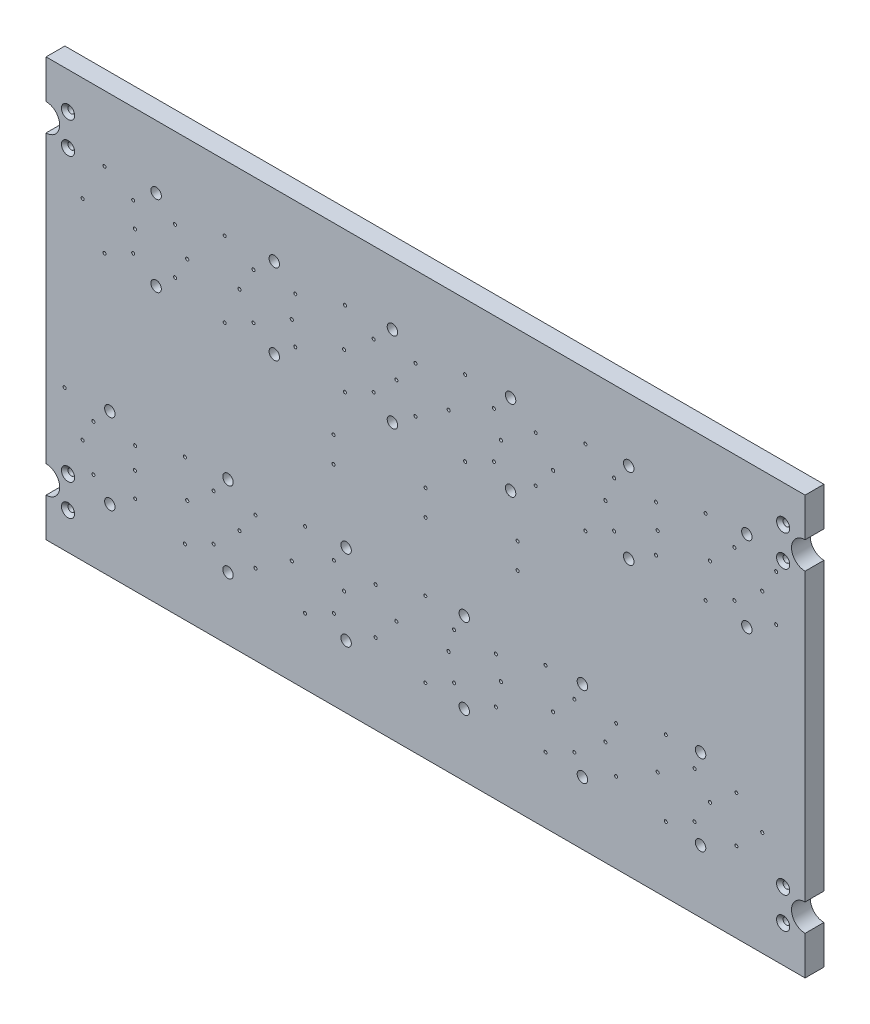
SolidWorks part; units mm, degrees
material "Balsa"
ref_plane "Спереди" through (0, 0, 0) normal (0, 0, 1) x (1, 0, 0)
ref_plane "Сверху" through (0, 0, 0) normal (0, 1, 0) x (1, 0, 0)
ref_plane "Справа" through (0, 0, 0) normal (1, 0, 0) x (0, 0, -1)
sketch "Sketch1" plane through (0, 0, 0) normal (0, 0, 1) x (1, 0, 0)
  line L1 (363, -200) -> (-363, -200)
  line L2 (363, -200) -> (363, 200)
  line L3 (363, 200) -> (-363, 200)
  line L4 (-363, -200) -> (-363, 200)
  line L5 (0, 200) -> (0, -200) construction
  line L6 (363, 0) -> (-363, 0) construction
  point P0 (0, 0)
  dimension "D1" = 400
  dimension "D2" = 726
extrude "BaseSheet" add sketch "Sketch1" along normal blind 18
sketch "Sketch2" plane through (0, 0, 18) normal (0, 0, 1) x (1, 0, 0)
  line L0 (-363, 200) -> (-363, -200) construction
  line L1 (363, -200) -> (363, 200) construction
  line L2 (0, 0) -> (-101.8318, 0) construction
  circle A0 centre (-363, 150) radius 13
  circle A1 centre (-363, -150) radius 13
  circle A2 centre (363, -150) radius 13
  circle A3 centre (363, 150) radius 13
  line M2 (-363, 200) -> (-363, -200)
  line M4 (363, -200) -> (363, 200)
  dimension "D2" = 26
  dimension "D1" = 300
extrude "Cut-Extrude1" cut sketch "Sketch2" against normal through all contours A0 M2 | A1 M2 | A2 M4 | A3 M4
hole_wizard "CSK for M6 Flat Head - Mount" positions "Sketch4" profile "Sketch5" countersink size "M6" standard "ANSI Metric" end condition through all
sketch "Sketch4" plane through (0, 0, 18) normal (0, 0, 1) x (1, 0, 0)
  line L0 (-363, 200) -> (-363, 163) construction
  line L1 (363, 200) -> (-363, 200) construction
  point P0 (-342, 165)
  point P2 (-342, 135)
  dimension "D1" = 30
  dimension "D2" = 21
  dimension "D3" = 35
sketch "Sketch5" plane through (-342, 165, 18) normal (1, 0, 0) x (0, -1, 0)
  line L0 (0, 0) -> (0, 18)
  line L1 (0, 18) -> (3.2, 18)
  line L2 (3.2, 18) -> (3.2, 3.1)
  line L3 (3.2, 3.1) -> (6.3, 0)
  line L5 (6.3, 0) -> (0, 0)
  line L6 (-3.2, 3.1) -> (-6.3, 0) construction
  line L11 (0, -6.35) -> (0, 107.95) construction
  dimension "Thru Hole Dia." = 6.4
  dimension "Thru Hole Depth" = 18
  dimension "Near C'Sink Dia." = 12.6
  dimension "Near C'Sink Angle" = 90
mirror "AnotherSideMount" about plane through (0, 0, 0) normal (0, 1, 0) of "CSK for M6 Flat Head - Mount"
mirror "FarSideMount" about plane through (0, 0, 0) normal (1, 0, 0) of "AnotherSideMount", "CSK for M6 Flat Head - Mount"
sketch "MatePoints" plane through (0, 0, 18) normal (0, 0, 1) x (1, 0, 0)
  line L0 (0, 0) -> (-73.454, 0) construction
  point P0 (-365, 150)
  point P1 (-365, -150)
  dimension "D1" = 365
  dimension "D2" = 300
hole_wizard "Ø10.0 (10) Diameter Hole harness" positions "Sketch8" profile "Sketch9" hole size "Ø10.0" standard "ANSI Metric" end condition through all
sketch "Sketch8" plane through (0, 0, 18) normal (0, 0, 1) x (1, 0, 0)
  line L4 (-363, -200) -> (363, -200) construction
  line L5 (363, -137) -> (363, 137) construction
  point P0 (-257.7194, 139.8086)
  point P2 (-257.7194, 62.8086)
  point P7 (-144.7194, 139.8086)
  point P9 (-31.7194, 139.8086)
  point P11 (81.2806, 139.8086)
  point P13 (194.2806, 139.8086)
  point P15 (307.2806, 139.8086)
  point P17 (-144.7194, 62.8086)
  point P19 (-31.7194, 62.8086)
  point P21 (81.2806, 62.8086)
  point P23 (194.2806, 62.8086)
  point P25 (307.2806, 62.8086)
  point P34 (-302, -63)
  point P36 (-302, -140)
  point P38 (-189, -140)
  point P40 (-189, -63)
  point P42 (-76, -63)
  point P44 (-76, -140)
  point P46 (37, -63)
  point P48 (37, -140)
  point P50 (150, -63)
  point P52 (150, -140)
  point P54 (263, -63)
  point P56 (263, -140)
  dimension "D3" = 113
  dimension "D4" = 113
  dimension "D5" = 113
  dimension "D6" = 113
  dimension "D10" = 113
  dimension "D11" = 113
  dimension "D12" = 113
  dimension "D9" = 113
  dimension "D7" = 60
  dimension "D2" = 113
  dimension "D8" = 100
  dimension "D13" = 113
  dimension "D14" = 77
  dimension "D15" = 77
sketch "Sketch9" plane through (-257.7194, 139.8086, 18) normal (1, 0, 0) x (0, -1, 0)
  line L0 (0, 0) -> (0, 18)
  line L1 (0, 18) -> (5, 18)
  line L2 (5, 18) -> (5, 0)
  line L5 (5, 0) -> (0, 0)
  line L11 (0, -6.35) -> (0, 107.95) construction
  dimension "Thru Hole Dia." = 10
  dimension "Thru Hole Depth" = 18
hole_wizard "Ø3.0 (3) Diameter Hole DIN rail" positions "Sketch10" profile "Sketch11" hole size "Ø3.0" standard "ANSI Metric" end condition through all
sketch "Sketch10" plane through (0, 0, 18) normal (0, 0, 1) x (1, 0, 0)
  line L0 (-363, 137) -> (-363, -137) construction
  line L1 (0, 0) -> (-78, 0) construction
  point P0 (-328, -100)
  point P2 (-328, 100)
  point P11 (-278, -100)
  point P12 (-278, 100)
  point P13 (-228, -100)
  point P14 (-228, 100)
  point P15 (-178, -100)
  point P16 (-178, 100)
  point P17 (-128, -100)
  point P18 (-128, 100)
  point P19 (-78, -100)
  point P20 (-78, 100)
  point P21 (-28, -100)
  point P22 (-28, 100)
  point P23 (22, -100)
  point P24 (22, 100)
  point P25 (72, -100)
  point P26 (72, 100)
  point P27 (122, -100)
  point P28 (122, 100)
  point P29 (172, -100)
  point P30 (172, 100)
  point P31 (222, -100)
  point P32 (222, 100)
  point P33 (272, -100)
  point P34 (272, 100)
  point P42 (322, -100)
  point P43 (322, 100)
  dimension "D2" = 35
  dimension "D3" = 200
  dimension "D1" = 14
sketch "Sketch11" plane through (-328, -100, 18) normal (1, 0, 0) x (0, -1, 0)
  line L0 (0, 0) -> (0, 18)
  line L1 (0, 18) -> (1.5, 18)
  line L2 (1.5, 18) -> (1.5, 0)
  line L5 (1.5, 0) -> (0, 0)
  line L11 (0, -6.35) -> (0, 107.95) construction
  dimension "Thru Hole Dia." = 3
  dimension "Thru Hole Depth" = 18
hole_wizard "Ø2.9 (2.9) Diameter Hole crate" positions "Sketch12" profile "Sketch13" hole size "Ø2.9" standard "ANSI Metric" end condition through all
sketch "Sketch12" plane through (0, 0, 18) normal (0, 0, 1) x (1, 0, 0)
  line L0 (-363, 200) -> (-363, 163) construction
  line L1 (363, 200) -> (-363, 200) construction
  line L3 (-363, 137) -> (-363, -137) construction
  point P0 (-279.65, 122.9)
  point P2 (-239.65, 122.9)
  point P4 (-279.65, 78.9)
  point P6 (-239.65, 78.9)
  point P14 (-307.15, 65.25)
  point P16 (-307.15, 137.25)
  point P22 (-317.75, -79.4)
  point P23 (-277.75, -79.4)
  point P24 (-317.75, -123.4)
  point P25 (-277.75, -123.4)
  point P27 (-345.25, -65.05)
  dimension "D1" = 44
  dimension "D2" = 40
  dimension "D3" = 13.65
  dimension "D4" = 27.5
  dimension "D5" = 72
  dimension "D6" = 123.35
  dimension "D7" = 77.1
  dimension "D8" = 44
  dimension "D9" = 40
  dimension "D10" = 17.75
  dimension "D11" = 27.5
  dimension "D12" = 14.35
  dimension "D14" = 158.3
sketch "Sketch13" plane through (-279.65, 122.9, 18) normal (1, 0, 0) x (0, -1, 0)
  line L0 (0, 0) -> (0, 18)
  line L1 (0, 18) -> (1.45, 18)
  line L2 (1.45, 18) -> (1.45, 0)
  line L5 (1.45, 0) -> (0, 0)
  line L11 (0, -6.35) -> (0, 107.95) construction
  dimension "Thru Hole Dia." = 2.9
  dimension "Thru Hole Depth" = 18
pattern_linear "CrateArray" count 6 spacing 115 along (1, 0, 0) of "Ø2.9 (2.9) Diameter Hole crate"
hole_wizard "Ø2.9 (2.9) for crates" positions "Sketch14" profile "Sketch15" hole size "Ø2.9" standard "ANSI Metric" end condition through all
sketch "Sketch14" plane through (0, 0, 18) normal (0, 0, 1) x (1, 0, 0)
  line L0 (-230.25, -66.5) -> (-230.25, -126.5709) construction
  circle A0 centre (-230.25, -65.05) radius 1.45 construction
  point P0 (-230.25, -137.05)
  point P2 (-115.25, -137.05)
  point P4 (-0.25, -137.05)
  point P6 (114.75, -137.05)
  point P8 (229.75, -137.05)
  dimension "D1" = 72
  dimension "D2" = 115
  dimension "D3" = 115
  dimension "D4" = 115
  dimension "D5" = 115
sketch "Sketch15" plane through (-230.25, -137.05, 18) normal (1, 0, 0) x (0, -1, 0)
  line L0 (0, 0) -> (0, 18)
  line L1 (0, 18) -> (1.45, 18)
  line L2 (1.45, 18) -> (1.45, 0)
  line L5 (1.45, 0) -> (0, 0)
  line L11 (0, -6.35) -> (0, 107.95) construction
  dimension "Thru Hole Dia." = 2.9
  dimension "Thru Hole Depth" = 18
hole_wizard "Ø2.9 (2.9) interface holes" positions "Sketch16" profile "Sketch17" hole size "Ø2.9" standard "ANSI Metric" end condition through all
sketch "Sketch16" plane through (0, 0, 18) normal (0, 0, 1) x (1, 0, 0)
  point P0 (0, 0)
  point P3 (0, 24.5)
  point P5 (-88, 0)
  point P7 (-88, 24.5)
  point P9 (88, 0)
  point P11 (88, 24.5)
  dimension "D1" = 24.5
  dimension "D2" = 88
  dimension "D3" = 88
sketch "Sketch17" plane through (0, 0, 18) normal (1, 0, 0) x (0, -1, 0)
  line L0 (0, 0) -> (0, 18)
  line L1 (0, 18) -> (1.45, 18)
  line L2 (1.45, 18) -> (1.45, 0)
  line L5 (1.45, 0) -> (0, 0)
  line L11 (0, -6.35) -> (0, 107.95) construction
  dimension "Thru Hole Dia." = 2.9
  dimension "Thru Hole Depth" = 18
equation "\"D4@Sketch8\"=\"D3@Sketch8\""
equation "\"D5@Sketch8\"=\"D3@Sketch8\""
equation "\"D6@Sketch8\"=\"D3@Sketch8\""
equation "\"D12@Sketch8\"=\"D3@Sketch8\""
equation "\"D11@Sketch8\"=\"D3@Sketch8\""
equation "\"D10@Sketch8\"=\"D3@Sketch8\""
